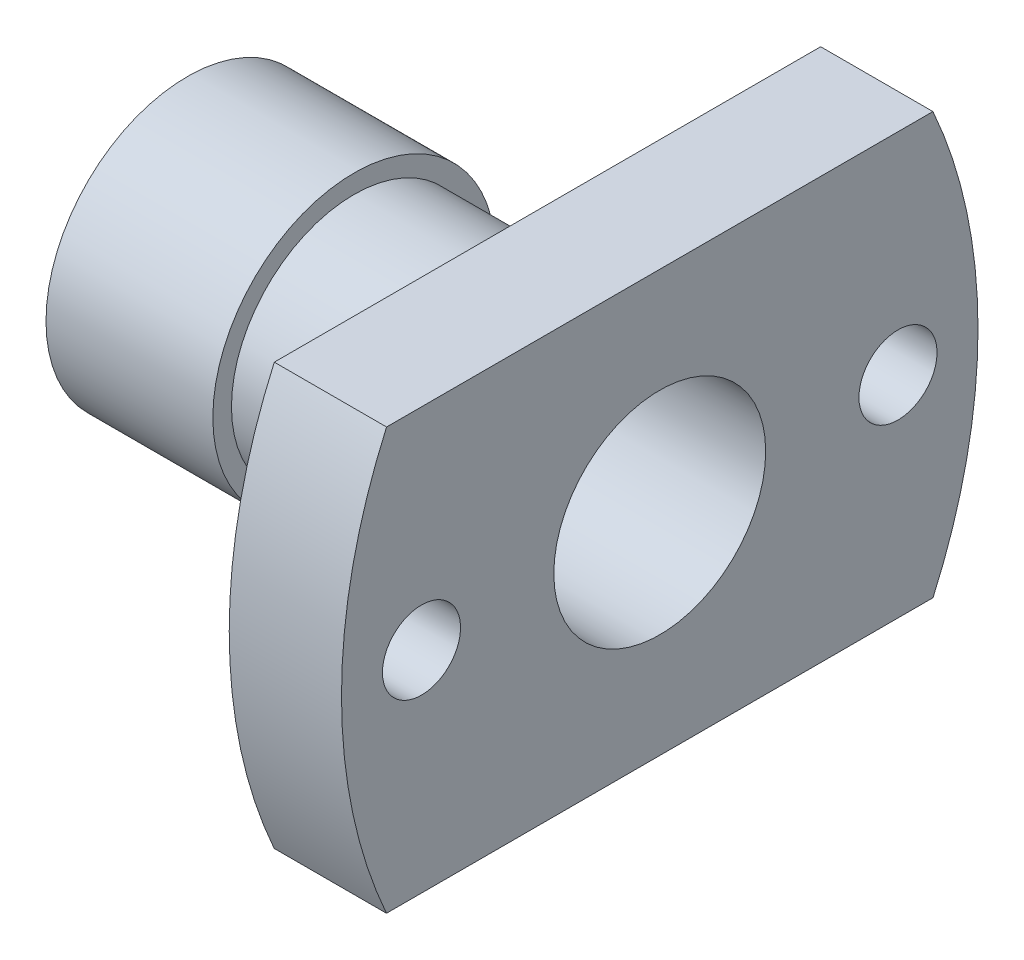
SolidWorks part; units mm, degrees
ref_plane "Front Plane" through (0, 0, 0) normal (0, 0, 1) x (1, 0, 0)
ref_plane "Top Plane" through (0, 0, 0) normal (0, 1, 0) x (1, 0, 0)
ref_plane "Right Plane" through (0, 0, 0) normal (1, 0, 0) x (0, 0, -1)
sketch "Sketch1" plane through (0, 0, 0) normal (1, 0, 0) x (0, 0, -1)
  line L0 (0, 0) -> (28.56, 0)
  line L1 (14.28, 0) -> (33.355, 0)
  line L2 (14.28, 0) -> (-4.795, 0)
  line L3 (14.28, 0) -> (14.28, 12.625)
  line L4 (14.28, 0) -> (14.28, -12.615)
  line L5 (-4.795, 0) -> (-4.795, 12.625)
  line L6 (-4.795, 12.625) -> (33.355, 12.625)
  line L7 (33.355, 12.625) -> (33.355, -12.615)
  line L8 (33.355, -12.615) -> (-4.795, -12.615)
  line L9 (-4.795, -12.615) -> (-4.795, 0)
  circle A0 centre (0, 0) radius 2.5
  circle A1 centre (28.56, 0) radius 2.5
  dimension "D1" = 28.56
extrude "Boss-Extrude1" add sketch "Sketch1" along normal blind 6.73 contours A0 L2 L9 L8 L4 | A0 L2 L3 L6 L5 | A1 L1 L7 L6 L3 L0 | A1 L0 L4 L8 L7 L1
sketch "Sketch3" plane through (0, 0, 0) normal (-1, 0, 0) x (0, 0, 1)
  line L0 (-16.1716, 27.6608) -> (-47.382, 12.2347)
  line L1 (-47.382, 12.2347) -> (-48.6301, -21.0385)
  line L2 (-48.6301, -21.0385) -> (-26.06, -19.9238)
  line L3 (-13.8892, 28.6761) -> (21.1414, 10.3676)
  line L4 (21.1414, 10.3676) -> (18.1454, -22.9303)
  line L5 (18.1454, -22.9303) -> (-1.5427, -18.7333)
  circle A0 centre (-2.5, 0) radius 30.855
  circle A1 centre (0, 0) radius 2.5 construction
  circle A2 centre (-26.06, 0) radius 30.855
  circle A3 centre (-28.56, 0) radius 2.5 construction
  line M2 (-33.355, 12.625) -> (-33.355, -12.615)
  line M3 (-33.355, -12.615) -> (4.795, -12.615)
  line M4 (4.795, -12.615) -> (4.795, 12.625)
  line M5 (4.795, 12.625) -> (-33.355, 12.625)
extrude "Cut-Extrude5" cut sketch "Sketch3" against normal blind 6.73 contours A2 M3 M4 | A2 M4 M5 | A0 M5 M2 | A0 M2 M3
sketch "Sketch4" plane through (0, 0, 0) normal (-1, 0, 0) x (0, 0, 1)
  line L0 (-14.28, 12.625) -> (-14.28, 0)
  line L1 (2.0939, 12.625) -> (-30.6539, 12.625) construction
  circle A0 centre (-14.28, 0) radius 7.35
extrude "Boss-Extrude2" add sketch "Sketch4" along normal blind 21.59
sketch "Sketch5" plane through (-21.59, 0, 0) normal (-1, 0, 0) x (0, 0, 1)
  circle A0 centre (-14.28, 0) radius 6.35
extrude "Cut-Extrude6" cut sketch "Sketch5" against normal through all
sketch "Sketch6" plane through (-21.59, 0, 0) normal (-1, 0, 0) x (0, 0, 1)
  circle A0 centre (-14.28, 0) radius 8.4666
  circle A1 centre (-14.28, 0) radius 7.35
extrude "Boss-Extrude3" add sketch "Sketch6" against normal blind 10
sketch "Sketch7" plane through (0, 0, 0) normal (-1, 0, 0) x (0, 0, 1)
  circle A0 centre (-28.56, 0) radius 2.34
  circle A1 centre (-28.56, 0) radius 2.5
  circle A2 centre (0, 0) radius 2.34
  circle A3 centre (0, 0) radius 2.5
  dimension "D1" = 4.68
  dimension "D2" = 4.68
extrude "Boss-Extrude4" add sketch "Sketch7" against normal through all
